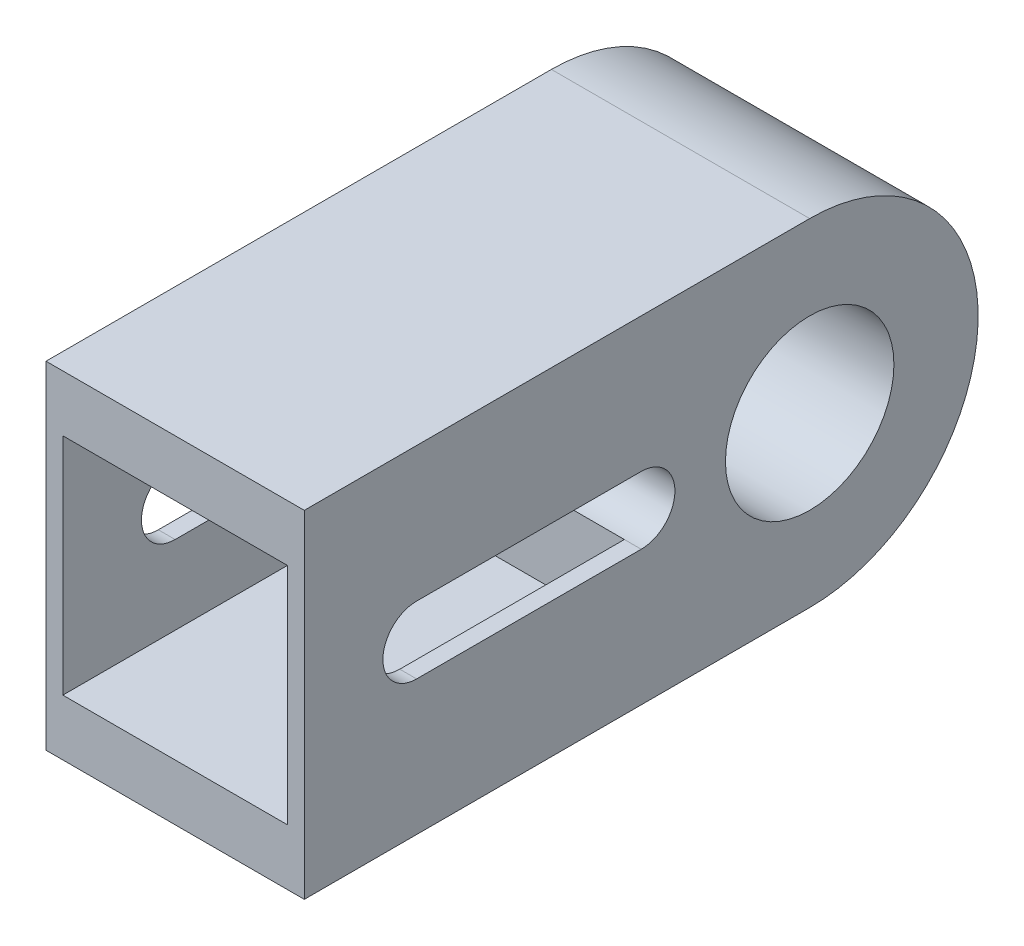
SolidWorks part; units mm, degrees
ref_plane "Front Plane" through (0, 0, 0) normal (0, 0, 1) x (1, 0, 0)
ref_plane "Top Plane" through (0, 0, 0) normal (0, 1, 0) x (1, 0, 0)
ref_plane "Right Plane" through (0, 0, 0) normal (1, 0, 0) x (0, 0, -1)
sketch "Sketch1" plane through (0, 0, 0) normal (1, 0, 0) x (0, 0, -1)
  line L0 (0, 0) -> (40.0928, 0) construction
  line L1 (-24.9536, 15) -> (20.0464, 15)
  line L2 (-24.9536, 15) -> (-24.9536, -15)
  line L3 (-24.9536, -15) -> (20.0464, -15)
  line L5 (-24.9536, 15) -> (24.9536, -15) construction
  line L6 (-24.9536, -15) -> (42.0872, 25.2993) construction
  arc A0 (20.0464, -15) -> (20.0464, 15) centre (20.0464, 0) ccw
  point P0 (0, 0)
  dimension "D3" = 35.0464
  dimension "D1" = 30
  dimension "D2" = 60
extrude "Boss-Extrude1" add sketch "Sketch1" against normal blind 23
sketch "Sketch2" plane through (0, 0, 0) normal (1, 0, 0) x (0, 0, -1)
  line L0 (-14.9536, 0) -> (5.0464, 0) construction
  line L1 (-14.9536, 3) -> (5.0464, 3)
  line L2 (-14.9536, -3) -> (5.0464, -3)
  line L3 (-24.9536, 15) -> (-24.9536, -15) construction
  arc A0 (-14.9536, 3) -> (-14.9536, -3) centre (-14.9536, 0) ccw
  arc A1 (5.0464, -3) -> (5.0464, 3) centre (5.0464, 0) ccw
  point P3 (-4.9536, 0)
  dimension "D1" = 3
  dimension "D2" = 20
  dimension "D3" = 10
extrude "Cut-Extrude1" cut sketch "Sketch2" against normal through all
sketch "Sketch3" plane through (0, 0, 0) normal (1, 0, 0) x (0, 0, -1)
  circle A0 centre (20.0464, 0) radius 7.5
  dimension "D1" = 15
extrude "Cut-Extrude2" cut sketch "Sketch3" against normal through all
sketch "Sketch4" plane through (0, 0, 24.9536) normal (0, 0, 1) x (1, 0, 0)
  line L0 (-23, 15) -> (0, 15) construction
  line L1 (-21.5, 10) -> (-1.5, 10)
  line L2 (-21.5, 10) -> (-21.5, -10)
  line L3 (-21.5, -10) -> (-1.5, -10)
  line L4 (-1.5, 10) -> (-1.5, -10)
  line L5 (-21.5, 10) -> (-1.5, -10) construction
  line L6 (-21.5, -10) -> (-1.5, 10) construction
  point P0 (-11.5, 0)
  point P10 (-11.5, 15)
  dimension "D1" = 20
  dimension "D2" = 20
extrude "Cut-Extrude3" cut sketch "Sketch4" against normal blind 30
